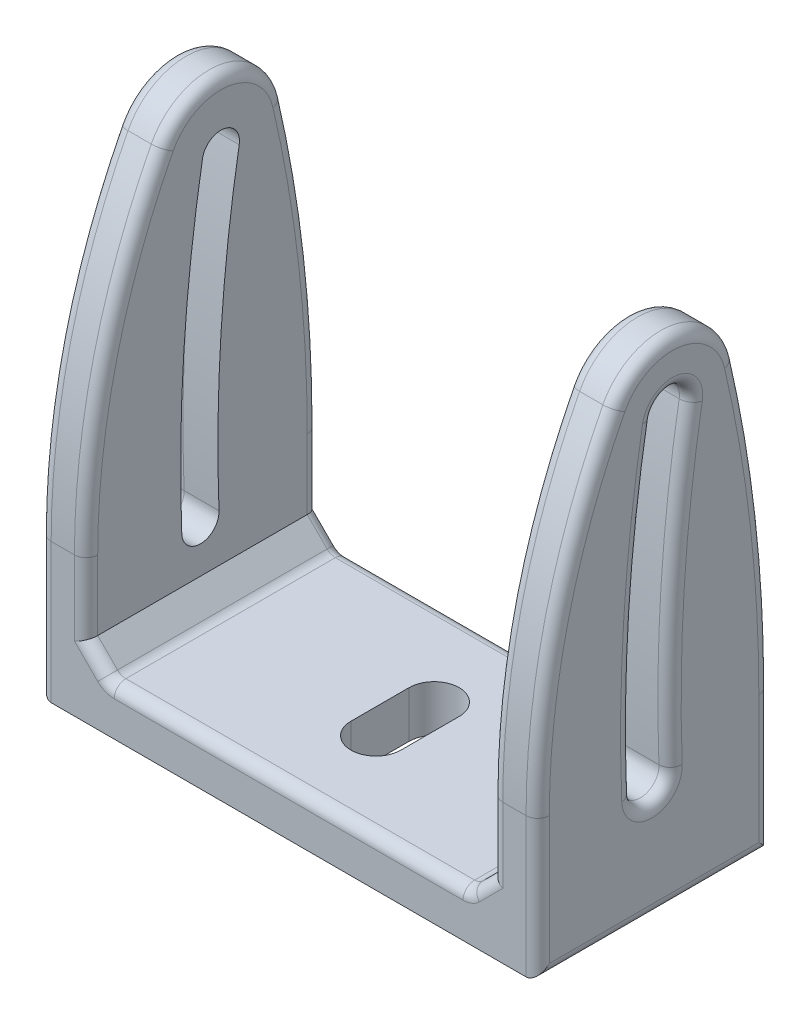
SolidWorks part; units mm, degrees
ref_plane "Front Plane" through (0, 0, 0) normal (0, 0, 1) x (1, 0, 0)
ref_plane "Top Plane" through (0, 0, 0) normal (0, 1, 0) x (1, 0, 0)
ref_plane "Right Plane" through (0, 0, 0) normal (1, 0, 0) x (0, 0, -1)
sketch "Sketch1" plane through (0, 0, 0) normal (1, 0, 0) x (0, 0, -1)
  line L1 (-10, -6) -> (10, -6)
  line L2 (-10, -6) -> (-10, 6)
  line L3 (-10, 6) -> (10, 6) construction
  line L4 (10, -6) -> (10, 6)
  line L5 (-10, -6) -> (10, 6) construction
  line L6 (-10, 6) -> (10, -6) construction
  line L8 (127.716, 9) -> (0, 9) construction
  line L9 (127.716, 9) -> (0, 17.408) construction
  line L10 (0, -6) -> (127.716, -6) construction
  line L11 (127.716, -6) -> (127.716, 9) construction
  line L12 (0, 17.408) -> (0, -6) construction
  line L13 (1.5785, 30.7119) -> (127.716, 9) construction
  line L14 (-0.1792, 4.012) -> (127.716, 9) construction
  arc A0 (-3.4022, 33.2717) -> (7.0344, 31.9742) centre (1.5785, 30.7119) cw
  arc A1 (1.5785, 30.7119) -> (-0.1792, 4.012) centre (127.716, 9) ccw construction
  arc A2 (0.0017, 30.9833) -> (-1.778, 3.9496) centre (127.716, 9) ccw
  arc A3 (3.1553, 30.4405) -> (1.4196, 4.0743) centre (127.716, 9) ccw
  arc A4 (3.1553, 30.4405) -> (0.0017, 30.9833) centre (1.5785, 30.7119) ccw
  arc A5 (-1.778, 3.9496) -> (1.4196, 4.0743) centre (-0.1792, 4.012) ccw
  arc A6 (-10, 6) -> (-3.4022, 33.2717) centre (49.6619, 6) cw
  arc A7 (10, 6) -> (7.0344, 31.9742) centre (-105.23, 6) ccw
  point P0 (0, 0)
  point P13 (0, 17.408)
  dimension "D2" = 8.408
  dimension "D4" = 4
  dimension "D8" = 12
  dimension "D7" = 1.6
  dimension "D1" = 12
  dimension "D3" = 20
  dimension "D5" = 15
  dimension "D6" = 127.716
extrude "Boss-Extrude1" add sketch "Sketch1" along normal blind 42.8
sketch "Sketch2" plane through (0, 0, 10) normal (0, 0, 1) x (1, 0, 0)
  line L0 (42.8, 36.3119) -> (0, 36.3119) construction
  line L1 (4, -2) -> (38.8, -2)
  line L2 (4, -2) -> (4, 36.3119)
  line L3 (4, 36.3119) -> (38.8, 36.3119)
  line L4 (38.8, -2) -> (38.8, 36.3119)
  line L5 (0, 36.3119) -> (4, 36.3119) construction
  line L6 (38.8, 36.3119) -> (42.8, 36.3119) construction
  line L7 (42.8, -6) -> (0, -6) construction
  dimension "D1" = 4
  dimension "D2" = 4
extrude "Cut-Extrude1" cut sketch "Sketch2" against normal through all
chamfer "Chamfer1" distance 2 angle 45 2 edges at (38.8, -2, 0) (4, -2, 0)
fillet "Fillet1" radius 1 38 edges at (38.8, 3, -10) (38.8, 3, 10) (4, 3, -10) (4, 3, 10) (38.8, 36.2691, -2.2694) (4, 36.2691, -2.2694) (5, -1, -10) (5, -1, 10) (37.8, -1, -10) (37.8, -1, 10) (6, -2, 0) (21.4, -2, -10) (36.8, -2, 0) (21.4, -2, 10) (42.8, 36.2691, -2.2694) (0, 36.2691, -2.2694) (38.8, 19.0715, -9.2562) (38.8, 20.0292, 8.3271) (4, 19.0715, -9.2562) (4, 20.0292, 8.3271) (0, 17.3029, -1.5965) (0, 2.4132, 0.1169) (0, 17.5131, 1.5965) (0, 32.2887, -1.8499) (0, 20.0292, 8.3271) (0, 0, 10) (0, -6, 0) (0, 0, -10) (0, 19.0715, -9.2562) (42.8, 2.4132, 0.1169) (42.8, 17.3029, -1.5965) (42.8, 32.2887, -1.8499) (42.8, 17.5131, 1.5965) (42.8, 0, -10) (42.8, -6, 0) (42.8, 0, 10) (42.8, 20.0292, 8.3271) (42.8, 19.0715, -9.2562)
sketch "Sketch3" plane through (0, -2, 0) normal (0, 1, 0) x (1, 0, 0)
  line L0 (21.4, -2.5) -> (21.4, 2.5) construction
  line L3 (19.25, -2.5) -> (19.25, 2.5)
  line L4 (23.55, -2.5) -> (23.55, 2.5)
  line L5 (21.4, 9) -> (21.4, -9) construction
  line L6 (36.3858, 9) -> (6.4142, 9) construction
  line L7 (6.4142, -9) -> (36.3858, -9) construction
  arc A0 (19.25, -2.5) -> (23.55, -2.5) centre (21.4, -2.5) ccw
  arc A1 (23.55, 2.5) -> (19.25, 2.5) centre (21.4, 2.5) ccw
  point P2 (21.4, 0)
  point P14 (0, 0)
  point P15 (21.4, 0)
  dimension "D1" = 4.3
  dimension "D2" = 5
extrude "Cut-Extrude2" cut sketch "Sketch3" against normal through all
